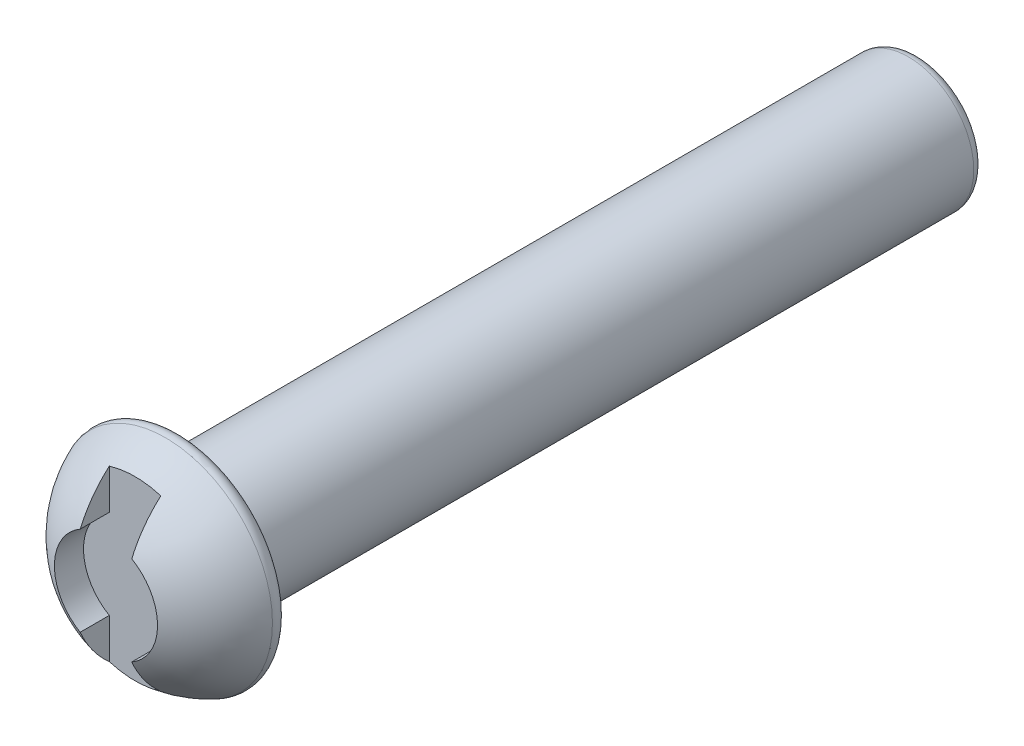
SolidWorks part; units mm, degrees
ref_plane "Front Plane" through (0, 0, 0) normal (0, 0, 1) x (1, 0, 0)
ref_plane "Top Plane" through (0, 0, 0) normal (0, 1, 0) x (1, 0, 0)
ref_plane "Right Plane" through (0, 0, 0) normal (1, 0, 0) x (0, 0, -1)
sketch "Sketch1" plane through (0, 0, 0) normal (1, 0, 0) x (0, 0, -1)
  line L0 (0, 0) -> (12, 0)
  line L1 (12, 0) -> (12, 0.95)
  line L2 (12, 0.95) -> (1.25, 0.95)
  line L3 (1.25, 0.95) -> (1.25, 1.625)
  arc A1 (1.25, 1.625) -> (0, 0) centre (1.6812, 0) ccw
  dimension "D1" = 12
  dimension "D2" = 0.95
  dimension "D3" = 1.625
  dimension "D4" = 1.25
revolve "Revolve1" add sketch "Sketch1" angle 360 about L0
sketch "Sketch2" plane through (0, 0, 0) normal (0, 0, 1) x (1, 0, 0)
  line L0 (0.375, -0.6495) -> (0.375, -1.9103)
  line L1 (-0.375, 1.9103) -> (0.375, 1.9103)
  line L2 (-0.375, 1.9103) -> (-0.375, 0.6495)
  line L3 (-0.375, -1.9103) -> (0.375, -1.9103)
  line L4 (0.375, 1.9103) -> (0.375, 0.6495)
  line L5 (-0.375, 1.9103) -> (0.375, -1.9103) construction
  line L6 (-0.375, -1.9103) -> (0.375, 1.9103) construction
  line L7 (-0.375, -0.6495) -> (-0.375, -1.9103)
  arc A0 (-0.375, 0.6495) -> (-0.375, -0.6495) centre (0, 0) ccw
  arc A1 (0.375, -0.6495) -> (0.375, 0.6495) centre (0, 0) ccw
  point P0 (0, 0)
  dimension "D2" = 1.5
  dimension "D1" = 0.75
extrude "Cut-Extrude1" cut sketch "Sketch2" against normal blind 0.6
fillet "Fillet1" radius 0.15 2 edges at (0.95, 0, -12) (1.625, 0, -1.25)
